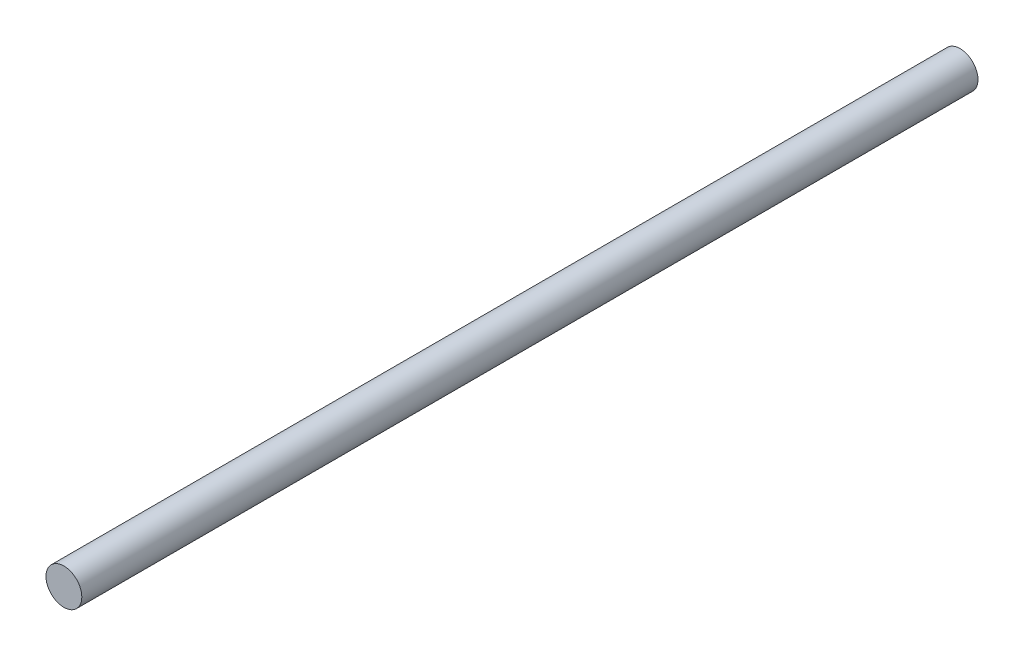
SolidWorks part; units mm, degrees
ref_plane "Front Plane" through (0, 0, 0) normal (0, 0, 1) x (1, 0, 0)
ref_plane "Top Plane" through (0, 0, 0) normal (0, 1, 0) x (1, 0, 0)
ref_plane "Right Plane" through (0, 0, 0) normal (1, 0, 0) x (0, 0, -1)
sketch "草圖1" plane through (0, 0, 0) normal (0, 0, 1) x (1, 0, 0)
  circle A0 centre (0, 0) radius 3
extrude "填料-伸長1" add sketch "草圖1" along normal blind 150
